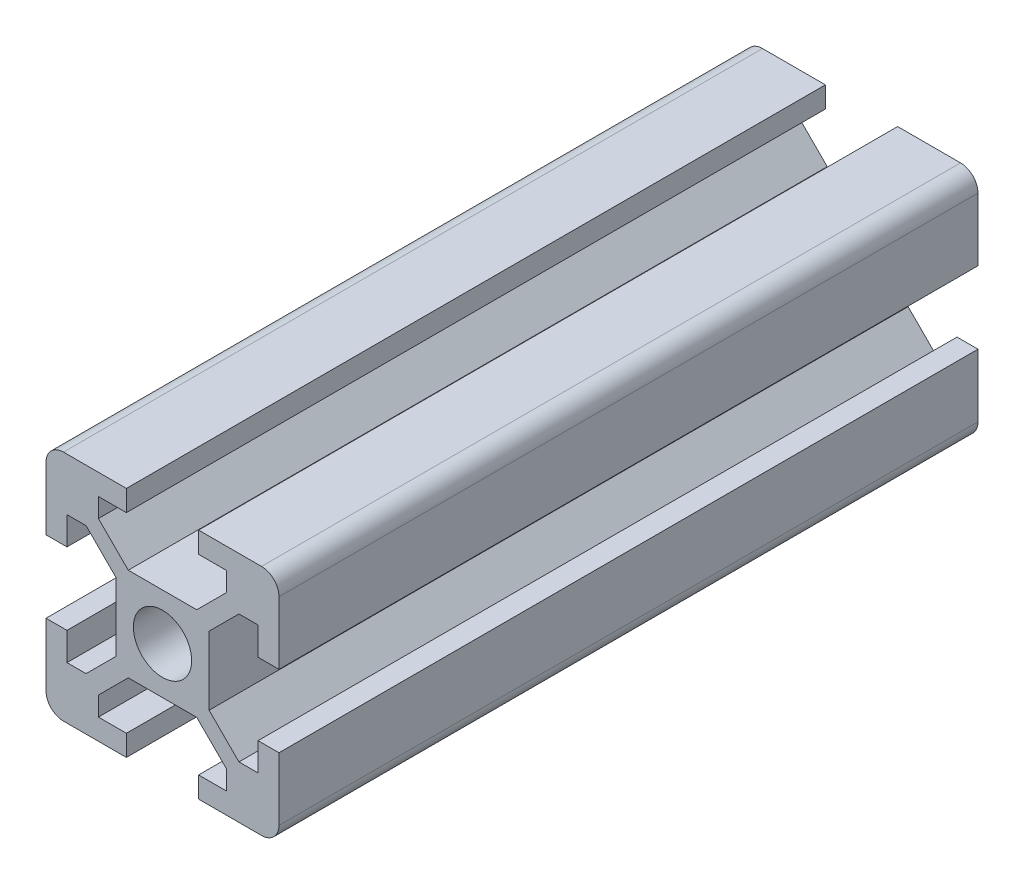
SolidWorks part; units mm, degrees
ref_plane "前视基准面" through (0, 0, 0) normal (0, 0, 1) x (1, 0, 0)
ref_plane "上视基准面" through (0, 0, 0) normal (0, 1, 0) x (1, 0, 0)
ref_plane "右视基准面" through (0, 0, 0) normal (1, 0, 0) x (0, 0, -1)
sketch "草图1" plane through (0, 0, 0) normal (0, 0, 1) x (1, 0, 0)
  line L0 (5.5, -8.2) -> (5.5, -6.5607)
  line L1 (-8.5, -10) -> (-3.1, -10)
  line L2 (-10, -8.5) -> (-10, -3.1)
  line L3 (-8.5, 10) -> (-3.1, 10)
  line L4 (10, -8.5) -> (10, -3.1)
  line L5 (-10, -10) -> (10, 10) construction
  line L6 (-10, 10) -> (10, -10) construction
  line L7 (8.2, 5.5) -> (6.5607, 5.5)
  line L8 (-2.9393, 4) -> (2.9393, 4)
  line L9 (4, 2.9393) -> (4, -2.9393)
  line L10 (2.9393, -4) -> (-2.9393, -4)
  line L11 (-4, -2.9393) -> (-4, 2.9393)
  line L12 (5.5, 6.5607) -> (5.5, 8.2)
  line L13 (6.5607, -5.5) -> (8.2, -5.5)
  line L14 (-8.2, -5.5) -> (-6.5607, -5.5)
  line L15 (-5.5, -6.5607) -> (-5.5, -8.2)
  line L16 (-5.5, 8.2) -> (-5.5, 6.5607)
  line L17 (-6.5607, 5.5) -> (-8.2, 5.5)
  line L18 (4, 2.9393) -> (6.5607, 5.5)
  line L19 (2.9393, 4) -> (5.5, 6.5607)
  line L20 (2.9393, -4) -> (5.5, -6.5607)
  line L21 (-4, 2.9393) -> (-6.5607, 5.5)
  line L22 (4, -2.9393) -> (6.5607, -5.5)
  line L23 (-2.9393, 4) -> (-5.5, 6.5607)
  line L24 (-4, -2.9393) -> (-6.5607, -5.5)
  line L25 (-2.9393, -4) -> (-5.5, -6.5607)
  line L26 (8.2, 3.1) -> (8.2, 5.5)
  line L27 (8.2, 3.1) -> (10, 3.1)
  line L28 (3.1, -8.2) -> (5.5, -8.2)
  line L29 (3.1, -8.2) -> (3.1, -10)
  line L30 (8.2, -3.1) -> (10, -3.1)
  line L31 (8.2, -3.1) -> (8.2, -5.5)
  line L32 (-3.1, -8.2) -> (-3.1, -10)
  line L33 (-3.1, -8.2) -> (-5.5, -8.2)
  line L34 (-8.2, -3.1) -> (-8.2, -5.5)
  line L35 (-8.2, -3.1) -> (-10, -3.1)
  line L36 (-8.2, 3.1) -> (-10, 3.1)
  line L37 (-8.2, 3.1) -> (-8.2, 5.5)
  line L38 (-3.1, 8.2) -> (-5.5, 8.2)
  line L39 (-3.1, 8.2) -> (-3.1, 10)
  line L40 (3.1, 8.2) -> (3.1, 10)
  line L41 (3.1, 8.2) -> (5.5, 8.2)
  line L42 (10, 3.1) -> (10, 8.5)
  line L43 (3.1, 10) -> (8.5, 10)
  line L44 (-10, 3.1) -> (-10, 8.5)
  line L45 (3.1, -10) -> (8.5, -10)
  arc A0 (8.5, -10) -> (10, -8.5) centre (8.5, -8.5) ccw
  arc A1 (-10, 8.5) -> (-8.5, 10) centre (-8.5, 8.5) cw
  arc A2 (-8.5, -10) -> (-10, -8.5) centre (-8.5, -8.5) cw
  arc A3 (8.5, 10) -> (10, 8.5) centre (8.5, 8.5) cw
  circle A4 centre (0, 0) radius 2.5
  point P0 (0, 0)
  point P39 (0, 0)
  point P56 (0, 0)
  point P73 (0, 0)
  dimension "D3" = 1.5
  dimension "D4" = 4
  dimension "D1" = 20
  dimension "D2" = 20
  dimension "D5" = 4
  dimension "D6" = 4
extrude "凸台-拉伸2" add sketch "草图1" against normal blind 60
